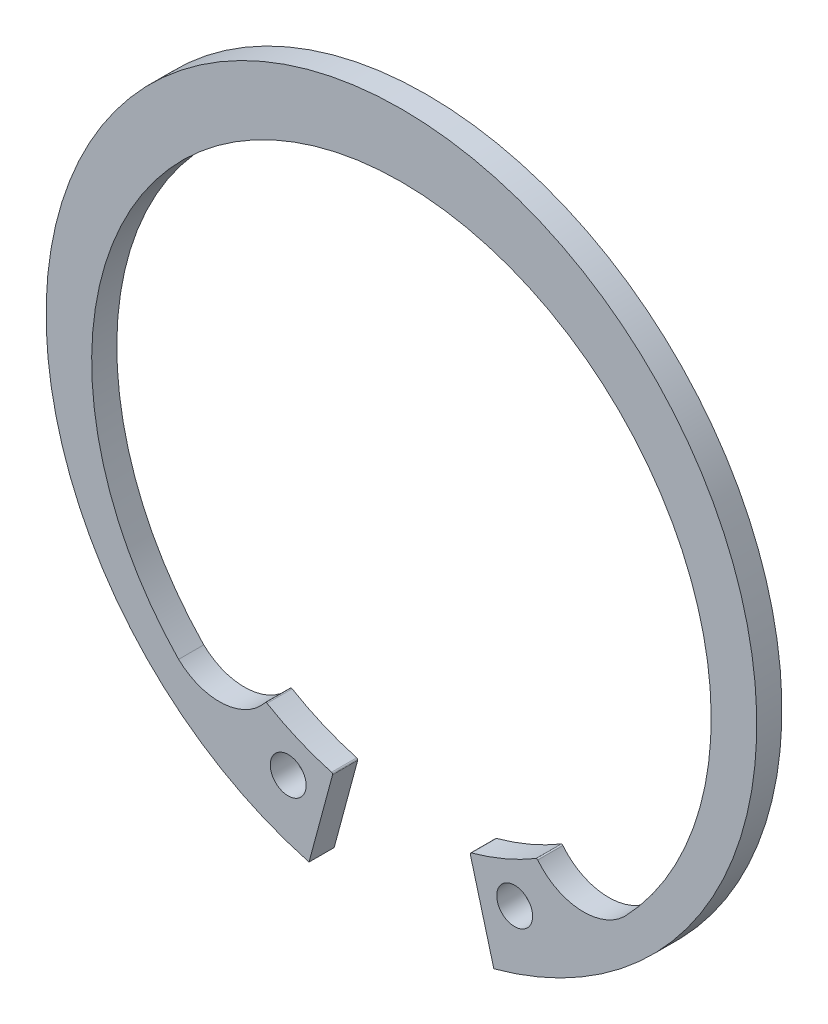
SolidWorks part; units mm, degrees
ref_plane "Plane1" through (0, 0, 0) normal (0, 0, 1) x (1, 0, 0)
ref_plane "Plane2" through (0, 0, 0) normal (0, 1, 0) x (1, 0, 0)
ref_plane "Plane3" through (0, 0, 0) normal (1, 0, 0) x (0, 0, -1)
extrude "Body" add sketch "BodySke" against normal blind 1.75
sketch "BodySke" plane through (0, 0, 0) normal (0, 0, 1) x (1, 0, 0)
  line L0 (-1.5431, 0) -> (1.5431, 0) construction
  line L1 (0, 0) -> (0, 20.35) construction
  line L2 (6.4361, -23.8985) -> (5.4001, -20.0515)
  line L3 (-6.4361, -23.8985) -> (-5.4001, -20.0515)
  line L4 (0, 0) -> (14.6742, -19.9307) construction
  line L5 (0, 0) -> (-14.6742, -19.9307) construction
  line L6 (-7.5614, -18.1749) -> (-8.2115, -20.5889) construction
  line L7 (7.6913, -18.6572) -> (8.0817, -20.1067) construction
  arc A0 (-5.4001, -20.0515) -> (-9.8643, -17.733) centre (-7.8865, -19.3819) ccw
  arc A1 (9.8643, -17.733) -> (5.4001, -20.0515) centre (7.8865, -19.3819) ccw
  arc A2 (13.3698, -18.159) -> (-13.3698, -18.159) centre (0, -1.2254) ccw construction
  arc A3 (6.4361, -23.8985) -> (-6.4361, -23.8985) centre (0, 0) ccw
  circle A4 centre (7.8865, -19.3819) radius 1.25
  circle A5 centre (-7.8865, -19.3819) radius 1.25
  circle A6 centre (7.8865, -19.3819) radius 2.575 construction
  arc A7 (13.447, -18.0978) -> (-13.447, -18.0978) centre (0, -1.2254) ccw
  arc A8 (-7.8865, -19.3819) -> (7.8865, -19.3819) centre (0, 0) ccw construction
  arc A9 (-13.447, -18.0978) -> (-9.8643, -17.733) centre (-11.8421, -16.0841) ccw
  arc A10 (9.8643, -17.733) -> (13.447, -18.0978) centre (11.8421, -16.0841) ccw
  dimension "GrooveDia" = 49.5
  dimension "TipRad" = 2.575
  dimension "HoleOffsetRad" = 20.925
  dimension "HoleDia" = 2.5
  dimension "FilletRad" = 2.575
  dimension "LargeRad" = 20.35
  dimension "SmallRad" = 22.55
  dimension "SmallAngle" = 72.726
  dimension "GapAngle" = 30.145
sketch "Clipboard" plane through (0, 0, 0) normal (0, 0, 1) x (1, 0, 0)
  line L0 (0, 0) -> (4.4, 0)
  line L1 (0, 0) -> (0, 2.2)
  line L2 (0, 0) -> (0, -6.4)
  circle A0 centre (0, 0) radius 1.25
  circle A1 centre (0, 0) radius 23.5
  dimension "HoleDia" = 2.5
  dimension "BoreDia" = 47
  dimension "LargeSection" = 4.4
  dimension "SmallSection" = 2.2
  dimension "LugSection" = 6.4
sketch "ModLugSke" plane through (0, 0, 0) normal (0, 0, 1) x (1, 0, 0)
  line L0 (6.4361, -23.8985) -> (4.7978, -17.815)
  line L1 (-6.4361, -23.8985) -> (-4.7978, -17.815)
  line L2 (12.689, -13.2556) -> (17.1146, -17.8788) construction
  line L3 (-12.689, -13.2556) -> (-17.1146, -17.8788) construction
  line L4 (-6.4361, -23.8985) -> (-5.4001, -20.0515) construction
  line L5 (5.4001, -20.0515) -> (6.4361, -23.8985) construction
  line L6 (0, 0) -> (0, -18.0732) construction
  line L7 (15.5173, -16.2102) -> (17.1146, -17.8788)
  line L8 (-17.1146, -17.8788) -> (-15.5173, -16.2102)
  arc A0 (6.4361, -23.8985) -> (17.1146, -17.8788) centre (0, 0) ccw
  arc A1 (-9.362, -15.7821) -> (-4.8678, -17.6926) centre (0, 0) ccw
  arc A2 (6.4361, -23.8985) -> (-6.4361, -23.8985) centre (0, 0) ccw construction
  arc A3 (9.8643, -17.733) -> (5.4001, -20.0515) centre (7.8865, -19.3819) ccw construction
  arc A4 (-9.362, -15.7821) -> (-9.4912, -15.8058) centre (-9.4131, -15.8681) ccw
  arc A5 (-15.5173, -16.2102) -> (-9.4912, -15.8058) centre (-12.689, -13.2556) ccw
  arc A6 (13.447, -18.0978) -> (-13.447, -18.0978) centre (0, -1.2254) ccw construction
  arc A7 (9.4912, -15.8058) -> (15.5173, -16.2102) centre (12.689, -13.2556) ccw
  arc A8 (4.8678, -17.6926) -> (9.362, -15.7821) centre (0, 0) ccw
  arc A9 (-17.1146, -17.8788) -> (-6.4361, -23.8985) centre (0, 0) ccw
  circle A10 centre (-7.8865, -19.3819) radius 1.25
  circle A11 centre (-7.8865, -19.3819) radius 1.25 construction
  circle A12 centre (7.8865, -19.3819) radius 1.25
  circle A13 centre (7.8865, -19.3819) radius 1.25 construction
  arc A14 (-4.8678, -17.6926) -> (-4.7978, -17.815) centre (-4.8943, -17.789) cw
  arc A15 (4.8678, -17.6926) -> (4.7978, -17.815) centre (4.8943, -17.789) ccw
  arc A16 (9.362, -15.7821) -> (9.4912, -15.8058) centre (9.4131, -15.8681) cw
  point P43 (4.7718, -17.7187)
  dimension "D1" = 0.1
  dimension "LugAng" = 61.353
extrude "ModLug" add sketch "ModLugSke" against normal through all
sketch "UnlSke" [suppressed] plane through (0, 0, 0) normal (0, 0, 1) x (1, 0, 0)
  line L0 (2.1178, -8.3352) -> (3.2259, -12.6966)
  line L1 (-2.1178, -8.3352) -> (-3.2259, -12.6966)
  line L2 (-3.2259, -12.6966) -> (-2.1422, -8.4315) construction
  line L3 (2.1422, -8.4315) -> (3.2259, -12.6966) construction
  arc A0 (2.1178, -8.3352) -> (-2.1178, -8.3352) centre (0, 0) ccw
  arc A1 (3.2259, -12.6966) -> (-3.2259, -12.6966) centre (0, 0) ccw
  arc A2 (3.2259, -12.6966) -> (-3.2259, -12.6966) centre (0, 0) ccw construction
  circle A4 centre (-4.4431, -9.5688) radius 1
  circle A5 centre (4.4431, -9.5688) radius 1
  circle A6 centre (4.4431, -9.5688) radius 1 construction
  circle A7 centre (-4.4431, -9.5688) radius 1 construction
  arc A8 (2.2134, -8.3103) -> (4.9183, -7.0548) centre (0, 0) ccw construction
extrude "Unlug" [suppressed] add sketch "UnlSke" against normal through all
equation "' \"BoreDia@Clipboard\" = 8"
equation "' \"Thickness@Body\" = 0.8"
equation "' \"GrooveDia@BodySke\" = 8.4"
equation "' \"LugSection@Clipboard\" = 2.4"
equation "' \"LargeSection@Clipboard\" = 1.1"
equation "' \"HoleDia@Clipboard\" = 1.0"
equation "' \"BoreDia@Clipboard\" = 25"
equation "' \"Thickness@Body\" = 1.2"
equation "' \"GrooveDia@BodySke\" = 26.2"
equation "' \"LugSection@Clipboard\" = 4.5"
equation "' \"LargeSection@Clipboard\" = 2.7"
equation "' \"HoleDia@Clipboard\" = 2"
equation "\"SmallSection@Clipboard\" = \"LargeSection@Clipboard\" * 0.5"
equation "\"TipRad@BodySke\" = (\"LugSection@Clipboard\" - (\"GrooveDia@BodySke\" / 2  -  \"BoreDia@Clipboard\" / 2 ) ) / 2"
equation "\"HoleOffsetRad@BodySke\" = (\"GrooveDia@BodySke\" / 2) - \"LugSection@Clipboard\"  + \"TipRad@BodySke\""
equation "\"LargeRad@BodySke\" =  \"GrooveDia@BodySke\" / 2 -  \"LargeSection@Clipboard\""
equation "\"SmallRad@BodySke\" =  \"GrooveDia@BodySke\" / 2 -  \"SmallSection@Clipboard\""
equation "\"HoleDia@BodySke\" =  \"HoleDia@Clipboard\""
equation "\"FilletRad@BodySke\" = \"TipRad@BodySke\" * 1.0"
equation "\"GapAngle@BodySke\" = 360 - 0.965 * 360 * ( \"BoreDia@Clipboard\" /  \"GrooveDia@BodySke\")"
equation "\"LugAng@ModLugSke\" = \"GapAngle@BodySke\"  + 2 * 360 * (\"LugSection@Clipboard\" / (\"BoreDia@Clipboard\" * 3.1416))"
